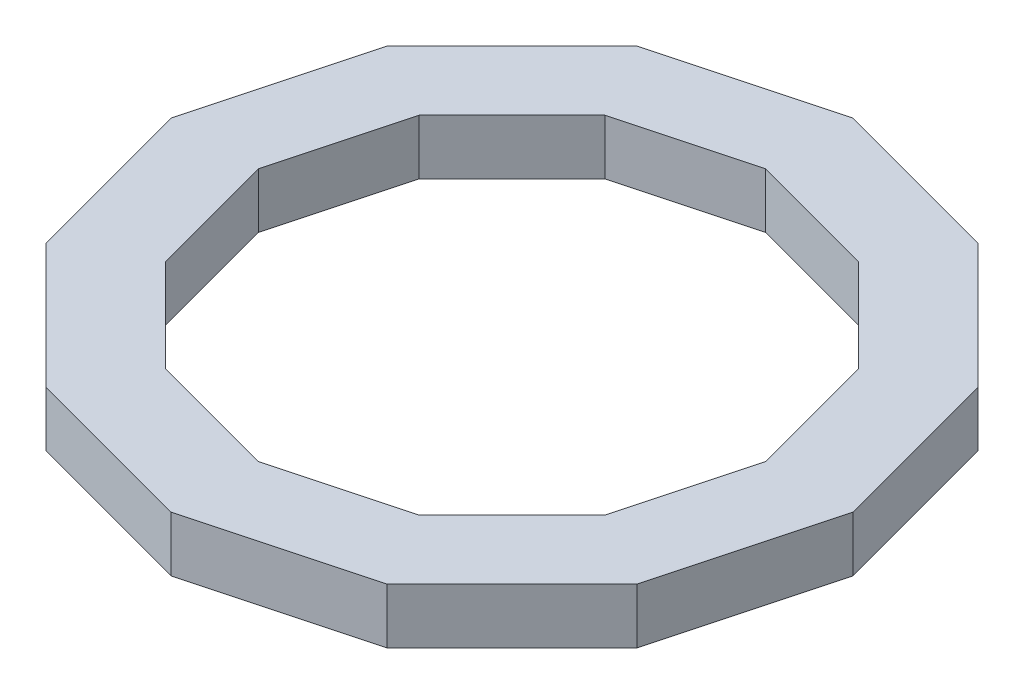
SolidWorks part; units mm, degrees
ref_plane "Front Plane" through (0, 0, 0) normal (0, 0, 1) x (1, 0, 0)
ref_plane "Top Plane" through (0, 0, 0) normal (0, 1, 0) x (1, 0, 0)
ref_plane "Right Plane" through (0, 0, 0) normal (1, 0, 0) x (0, 0, -1)
sketch "Sketch1" plane through (0, 0, 0) normal (0, 1, 0) x (1, 0, 0)
  line L0 (0, 0) -> (87.5253, 0) construction
  line L1 (87.5253, 0) -> (75.7991, 43.7626)
  line L2 (75.7991, 43.7626) -> (43.7626, 75.7991)
  line L3 (43.7626, 75.7991) -> (0, 87.5253)
  line L4 (0, 87.5253) -> (-43.7626, 75.7991)
  line L5 (-43.7626, 75.7991) -> (-75.7991, 43.7626)
  line L6 (-75.7991, 43.7626) -> (-87.5253, 0)
  line L7 (-87.5253, 0) -> (-75.7991, -43.7626)
  line L8 (-75.7991, -43.7626) -> (-43.7626, -75.7991)
  line L9 (-43.7626, -75.7991) -> (0, -87.5253)
  line L10 (0, -87.5253) -> (43.7626, -75.7991)
  line L11 (43.7626, -75.7991) -> (75.7991, -43.7626)
  line L12 (75.7991, -43.7626) -> (87.5253, 0)
  line L13 (117.7657, 0) -> (101.9881, 58.8828)
  line L14 (101.9881, 58.8828) -> (58.8828, 101.9881)
  line L15 (58.8828, 101.9881) -> (0, 117.7657)
  line L16 (0, 117.7657) -> (-58.8828, 101.9881)
  line L17 (-58.8828, 101.9881) -> (-101.9881, 58.8828)
  line L18 (-101.9881, 58.8828) -> (-117.7657, 0)
  line L19 (-117.7657, 0) -> (-101.9881, -58.8828)
  line L20 (-101.9881, -58.8828) -> (-58.8828, -101.9881)
  line L21 (-58.8828, -101.9881) -> (0, -117.7657)
  line L22 (0, -117.7657) -> (58.8828, -101.9881)
  line L23 (58.8828, -101.9881) -> (101.9881, -58.8828)
  line L24 (101.9881, -58.8828) -> (117.7657, 0)
  circle A0 centre (0, 0) radius 84.5429 construction
  circle A1 centre (0, 0) radius 113.7529 construction
  dimension "D1" = 29.21
  dimension "D2" = 60.96
extrude "Boss-Extrude1" add sketch "Sketch1" along normal blind 19.05
